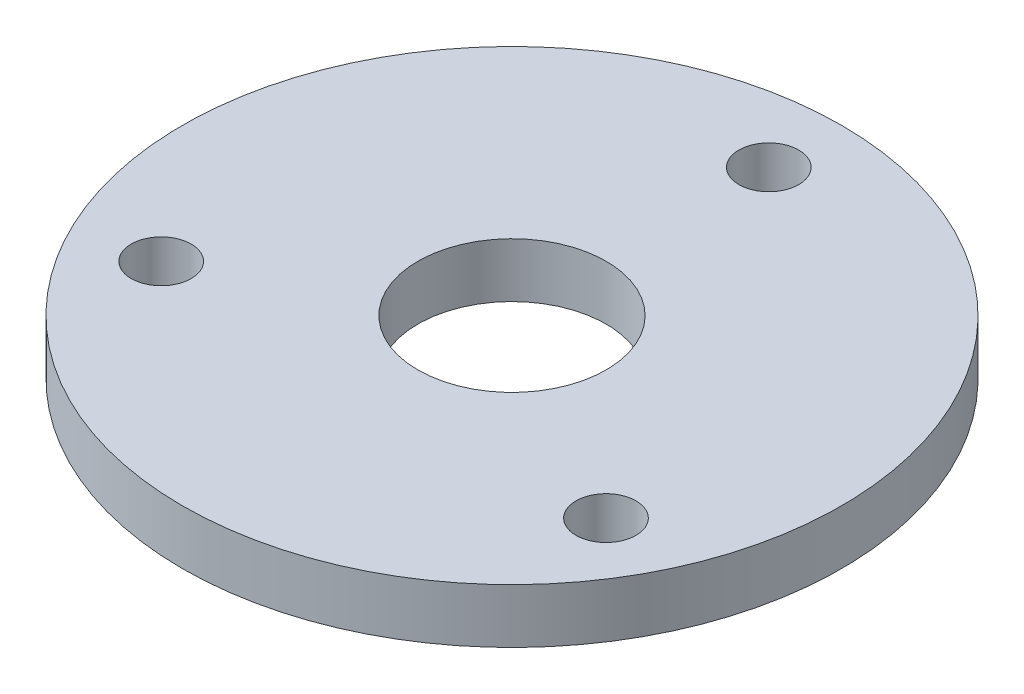
SolidWorks part; units mm, degrees
ref_plane "Front Plane" through (0, 0, 0) normal (0, 0, 1) x (1, 0, 0)
ref_plane "Top Plane" through (0, 0, 0) normal (0, 1, 0) x (1, 0, 0)
ref_plane "Right Plane" through (0, 0, 0) normal (1, 0, 0) x (0, 0, -1)
sketch "Sketch1" plane through (0, 0, 0) normal (0, 1, 0) x (1, 0, 0)
  line L1 (837.1525, 541.0169) -> (1029.1525, 541.0169)
  line L2 (837.1525, 541.0169) -> (837.1525, 349.0169)
  line L3 (837.1525, 349.0169) -> (1029.1525, 349.0169)
  line L4 (1029.1525, 541.0169) -> (1029.1525, 349.0169)
  line L5 (933.1525, 541.0169) -> (933.1525, 349.0169)
  line L6 (837.1525, 445.0169) -> (1029.1525, 445.0169)
  dimension "D1" = 192
  dimension "D2" = 192
sketch "Sketch5" plane through (0, 0, 0) normal (0, 1, 0) x (1, 0, 0)
  line L0 (837.1525, 445.0169) -> (1029.1525, 445.0169) construction
  line L1 (933.1525, 541.0169) -> (933.1525, 349.0169) construction
  circle A0 centre (933.1525, 445.0169) radius 38.5
  dimension "D1" = 77
extrude "Boss-Extrude2" add sketch "Sketch5" along normal blind 6.36
sketch "Sketch7" plane through (0, 6.36, 0) normal (0, 1, 0) x (1, 0, 0)
  line L0 (933.1525, 541.0169) -> (933.1525, 349.0169) construction
  line L1 (837.1525, 445.0169) -> (1029.1525, 445.0169) construction
  circle A0 centre (933.1525, 445.0169) radius 30 construction
  circle A1 centre (933.1525, 475.0169) radius 3.5
  circle A2 centre (-81.1803, -1030.6423) radius 30 construction
  circle A3 centre (-55.1995, -1045.6423) radius 3.5
  circle A4 centre (-851.9723, 585.6253) radius 30 construction
  circle A5 centre (-877.953, 570.6253) radius 3.5
  circle A6 centre (959.1333, 430.0169) radius 3.5
  circle A7 centre (907.1718, 430.0169) radius 3.5
  point P4 (957.9962, 427.2744)
  point P9 (0, 0)
  point P19 (0, 0)
  point P24 (933.1525, 445.0169)
  dimension "D2" = 60
  dimension "D3" = 3
  dimension "D1" = 7
  dimension "D4" = 3
extrude "Cut-Extrude3" cut sketch "Sketch7" against normal through all
sketch "Sketch8" plane through (0, 6.36, 0) normal (0, 1, 0) x (1, 0, 0)
  line L1 (837.1525, 445.0169) -> (1029.1525, 445.0169) construction
  circle A0 centre (933.1525, 445.0169) radius 11
  point P5 (0, 0)
  point P6 (933.1525, 445.0169)
  point P7 (0, 0)
  dimension "D1" = 22
extrude "Cut-Extrude4" cut sketch "Sketch8" against normal through all
